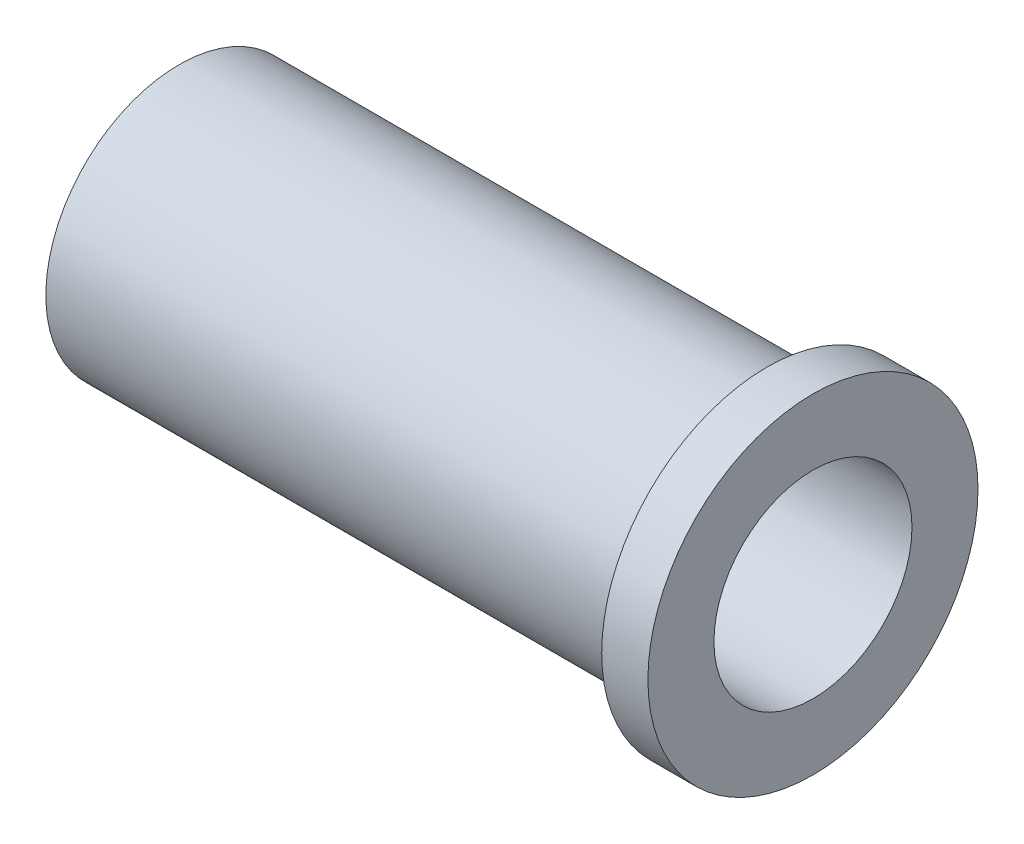
SolidWorks part; units mm, degrees
ref_plane "Front Plane" through (0, 0, 0) normal (0, 0, 1) x (1, 0, 0)
ref_plane "Top Plane" through (0, 0, 0) normal (0, 1, 0) x (1, 0, 0)
ref_plane "Right Plane" through (0, 0, 0) normal (1, 0, 0) x (0, 0, -1)
sketch "Sketch1" plane through (0, 0, 0) normal (1, 0, 0) x (0, 0, -1)
  circle A0 centre (0, 0) radius 10.1
  circle A1 centre (0, 0) radius 7.5
  dimension "D1" = 20.2
  dimension "D2" = 15
extrude "Boss-Extrude1" add sketch "Sketch1" along normal blind 48
sketch "Sketch2" plane through (48, 0, 0) normal (1, 0, 0) x (0, 0, -1)
  circle A0 centre (0, 0) radius 12.5
  circle A1 centre (0, 0) radius 10.1 construction
  circle A2 centre (0, 0) radius 10.1
  dimension "D1" = 25
extrude "Boss-Extrude2" add sketch "Sketch2" against normal blind 3.5
